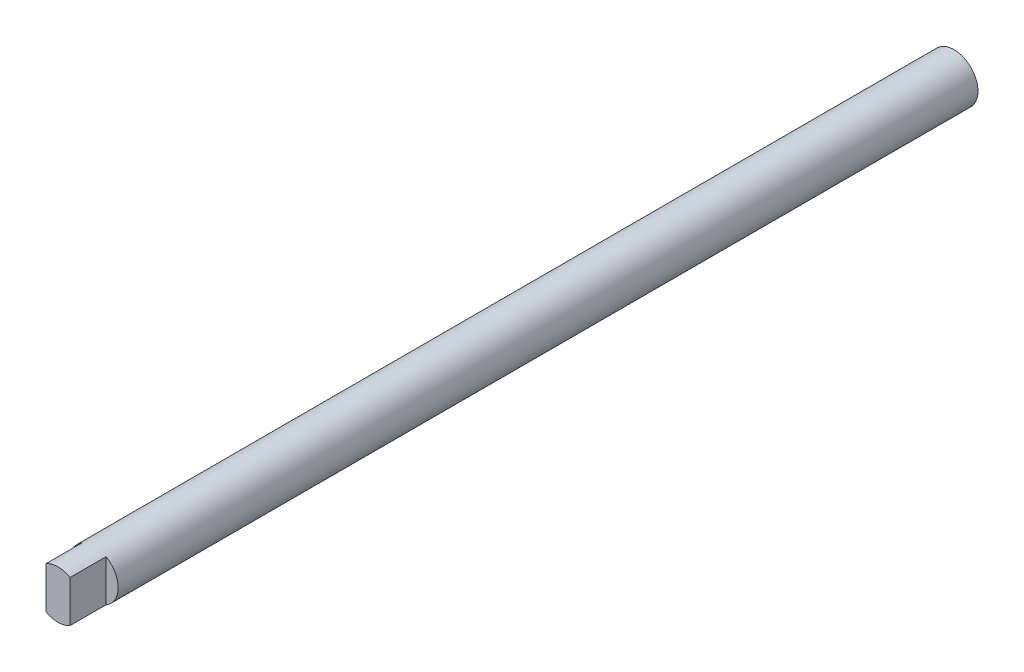
SolidWorks part; units mm, degrees
material "铸造碳钢"
ref_plane "前视基准面" through (0, 0, 0) normal (0, 0, 1) x (1, 0, 0)
ref_plane "上视基准面" through (0, 0, 0) normal (0, 1, 0) x (1, 0, 0)
ref_plane "右视基准面" through (0, 0, 0) normal (1, 0, 0) x (0, 0, -1)
sketch "草图1" plane through (0, 0, 0) normal (0, 0, 1) x (1, 0, 0)
  circle A0 centre (0, 0) radius 4
  dimension "D1" = 8
extrude "凸台-拉伸1" add sketch "草图1" along normal mid plane 149
sketch "草图2" plane through (0, 0, 0) normal (0, 1, 0) x (1, 0, 0)
  line L0 (0, 0) -> (0, 87.7309) construction
  line L1 (2, -68.5) -> (4, -74.5) construction
  line L2 (-2, -74.5) -> (-4, -74.5)
  line L3 (-2, -74.5) -> (-2, -68.5)
  line L4 (-2, -68.5) -> (-4, -68.5)
  line L5 (-4, -74.5) -> (-4, -68.5)
  line L6 (-2, -74.5) -> (-4, -68.5) construction
  line L7 (-2, -68.5) -> (-4, -74.5) construction
  line L8 (2, -74.5) -> (4, -68.5) construction
  line L9 (4, -74.5) -> (4, -68.5)
  line L10 (2, -68.5) -> (4, -68.5)
  line L11 (2, -74.5) -> (2, -68.5)
  line L12 (2, -74.5) -> (4, -74.5)
  line L13 (-4, -74.5) -> (4, -74.5) construction
  line L14 (-4, 74.5) -> (-4, -74.5) construction
  point P3 (-3, -71.5)
  point P13 (3, -71.5)
  dimension "D1" = 4
  dimension "D2" = 6
extrude "切除-拉伸1" cut sketch "草图2" against normal through all both and the other way through all
